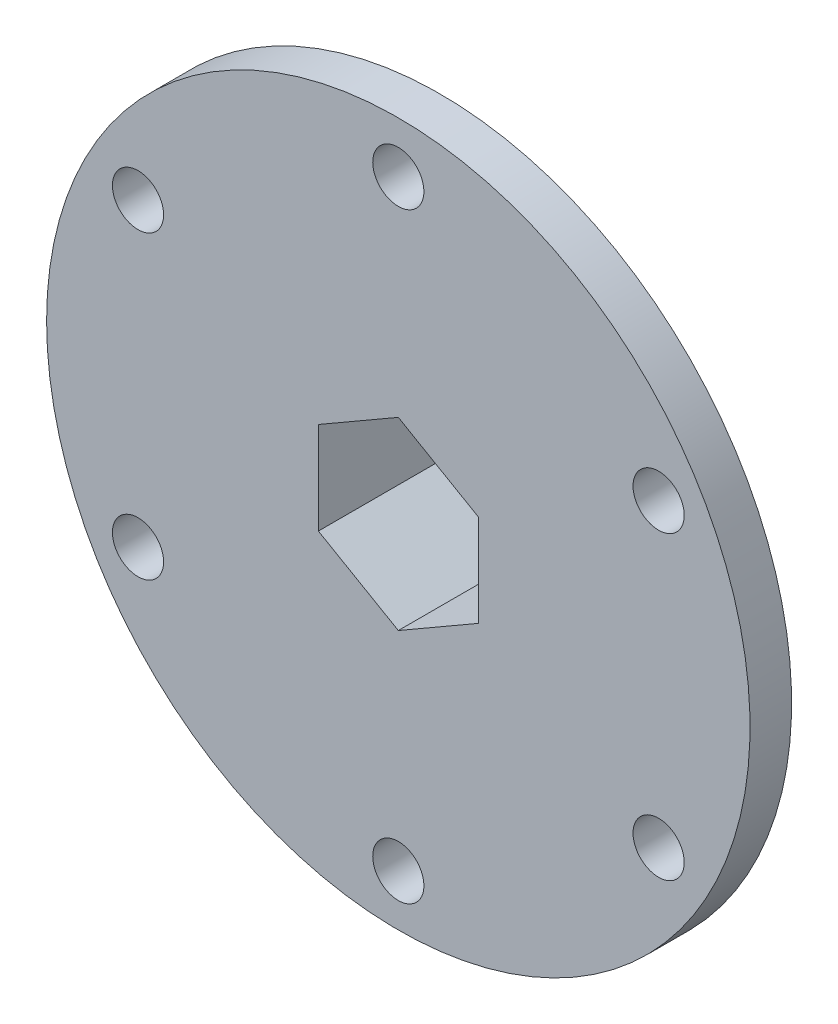
SolidWorks part; units mm, degrees
ref_plane "Front Plane" through (0, 0, 0) normal (0, 0, 1) x (1, 0, 0)
ref_plane "Top Plane" through (0, 0, 0) normal (0, 1, 0) x (1, 0, 0)
ref_plane "Right Plane" through (0, 0, 0) normal (1, 0, 0) x (0, 0, -1)
sketch "Sketch1" plane through (0, 0, 0) normal (0, 0, 1) x (1, 0, 0)
  line L0 (0, 0) -> (0, 23.876) construction
  line L1 (0, -7.3323) -> (6.35, -3.6662) construction
  line L2 (6.35, -3.6662) -> (6.35, 3.6662) construction
  line L3 (6.35, 3.6662) -> (0, 7.3323) construction
  line L4 (0, 7.3323) -> (-6.35, 3.6662) construction
  line L5 (-6.35, 3.6662) -> (-6.35, -3.6662) construction
  line L6 (-6.35, -3.6662) -> (0, -7.3323) construction
  circle A0 centre (0, 0) radius 27.94
  circle A1 centre (0, 0) radius 6.35 construction
  circle A2 centre (0, 23.876) radius 2.032
  circle A3 centre (20.6772, 11.938) radius 2.032
  circle A4 centre (20.6772, -11.938) radius 2.032
  circle A5 centre (0, -23.876) radius 2.032
  circle A6 centre (-20.6772, -11.938) radius 2.032
  circle A7 centre (-20.6772, 11.938) radius 2.032
  point P25 (0, 0)
  dimension "D2" = 55.88
  dimension "D3" = 4.064
  dimension "D4" = 23.876
  dimension "D5" = 12.7
  dimension "D1" = 6
extrude "Boss-Extrude1" add sketch "Sketch1" along normal blind 3.302
sketch "Sketch2" plane through (0, 0, 0) normal (0, 0, -1) x (-1, 0, 0)
  circle A0 centre (0, 0) radius 14.224
  dimension "D1" = 28.448
extrude "Boss-Extrude2" add sketch "Sketch2" along normal blind 9.398
sketch "Sketch3" plane through (0, 0, -9.398) normal (0, 0, -1) x (-1, 0, 0)
  line L0 (0, 0) -> (0, 23.876) construction
  line L1 (0, 7.3323) -> (-6.35, 3.6662)
  line L2 (-6.35, 3.6662) -> (-6.35, -3.6662)
  line L3 (-6.35, -3.6662) -> (0, -7.3323)
  line L4 (0, -7.3323) -> (6.35, -3.6662)
  line L5 (6.35, -3.6662) -> (6.35, 3.6662)
  line L6 (6.35, 3.6662) -> (0, 7.3323)
  circle A0 centre (0, 0) radius 6.35 construction
  dimension "D1" = 12.7
extrude "Cut-Extrude1" cut sketch "Sketch3" against normal up to surface (12.7 mm away) up to face at (-18.6452, -11.938, 3.302)
